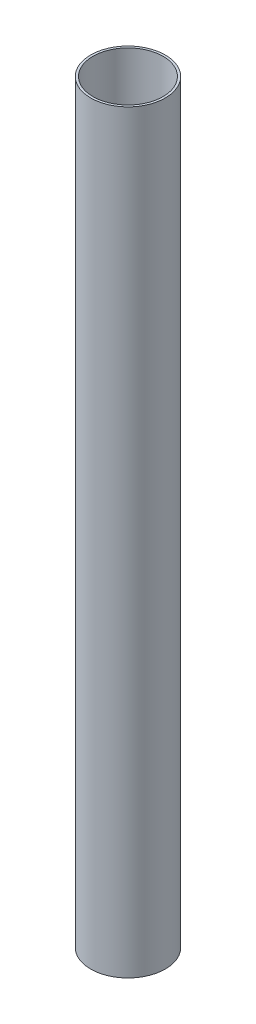
SolidWorks part; units mm, degrees
ref_plane "Front Plane" through (0, 0, 0) normal (0, 0, 1) x (1, 0, 0)
ref_plane "Top Plane" through (0, 0, 0) normal (0, 1, 0) x (1, 0, 0)
ref_plane "Right Plane" through (0, 0, 0) normal (1, 0, 0) x (0, 0, -1)
sketch "Sketch1" plane through (0, 0, 0) normal (0, 1, 0) x (1, 0, 0)
  circle A0 centre (0, 0) radius 27
  circle A1 centre (0, 0) radius 25.35
  dimension "D1" = 54
  dimension "D2" = 50.7
extrude "Boss-Extrude1" add sketch "Sketch1" along normal blind 546.1
